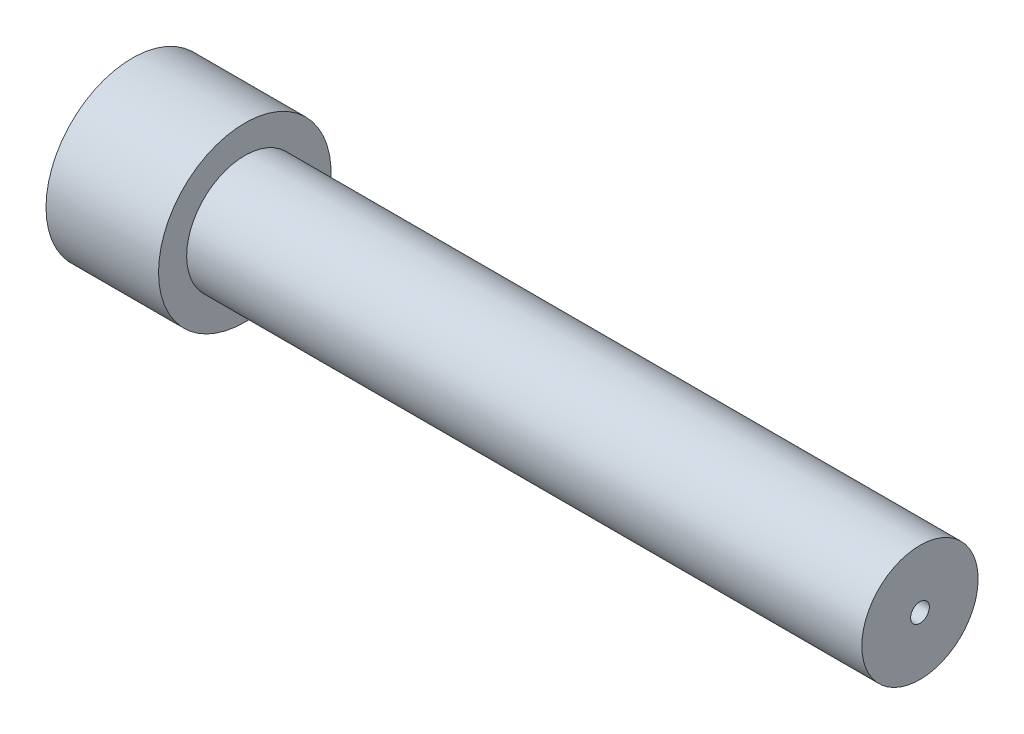
SolidWorks part; units mm, degrees
ref_plane "Front Plane" through (0, 0, 0) normal (0, 0, 1) x (1, 0, 0)
ref_plane "Top Plane" through (0, 0, 0) normal (0, 1, 0) x (1, 0, 0)
ref_plane "Right Plane" through (0, 0, 0) normal (1, 0, 0) x (0, 0, -1)
sketch "Sketch1" plane through (0, 0, 0) normal (0, 0, 1) x (1, 0, 0)
  line L0 (0, 0) -> (4702.007, 0) construction
  line L1 (0, 0) -> (0, 2.3)
  line L2 (0, 2.3) -> (3, 2.3)
  line L3 (3, 2.3) -> (3, 1.55)
  line L4 (3, 1.55) -> (21, 1.55)
  line L5 (21, 1.55) -> (21, 0.25)
  line L6 (21, 0.25) -> (16, 0.25)
  line L7 (16, 0.25) -> (16, 0)
  line L8 (16, 0) -> (0, 0)
  dimension "D1" = 4.6
  dimension "D2" = 3.1
  dimension "D3" = 0.5
  dimension "D4" = 5
  dimension "D5" = 18
  dimension "D6" = 3
revolve "Revolve1" add sketch "Sketch1" angle 360 about L0
